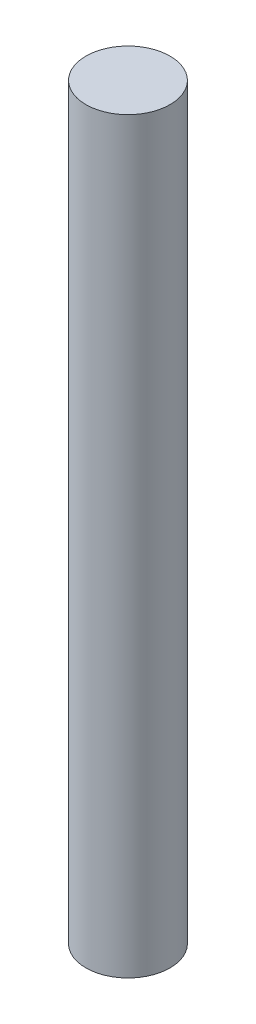
SolidWorks part; units mm, degrees
ref_plane "前视基准面" through (0, 0, 0) normal (0, 0, 1) x (1, 0, 0)
ref_plane "上视基准面" through (0, 0, 0) normal (0, 1, 0) x (1, 0, 0)
ref_plane "右视基准面" through (0, 0, 0) normal (1, 0, 0) x (0, 0, -1)
other "Configuration Table"
sketch "草图1" plane through (0, 0, 0) normal (0, 1, 0) x (1, 0, 0)
  circle A0 centre (0, 0) radius 2.25
  dimension "D1" = 4.5
extrude "凸台-拉伸1" add sketch "草图1" along normal blind 40
